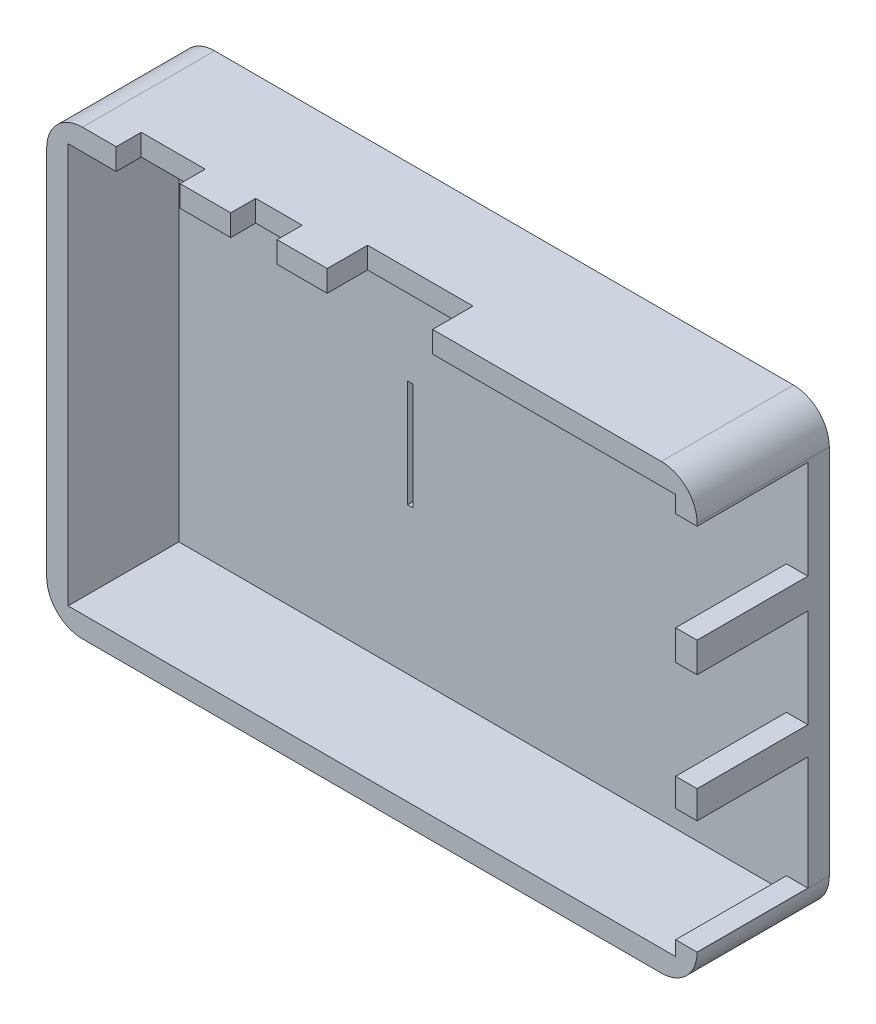
SolidWorks part; units mm, degrees
ref_plane "Front Plane" through (0, 0, 0) normal (0, 0, 1) x (1, 0, 0)
ref_plane "Top Plane" through (0, 0, 0) normal (0, 1, 0) x (1, 0, 0)
ref_plane "Right Plane" through (0, 0, 0) normal (1, 0, 0) x (0, 0, -1)
sketch "Sketch1" plane through (0, 0, 0) normal (0, 0, 1) x (1, 0, 0)
  line L1 (-45.5, -31) -> (45.5, -31)
  line L2 (-45.5, -31) -> (-45.5, 31)
  line L3 (-45.5, 31) -> (45.5, 31)
  line L4 (45.5, -31) -> (45.5, 31)
  line L5 (-45.5, -31) -> (45.5, 31) construction
  line L6 (-45.5, 31) -> (45.5, -31) construction
  point P0 (0, 0)
  dimension "D1" = 62
  dimension "D2" = 91
extrude "Boss-Extrude1" add sketch "Sketch1" along normal blind 3
sketch "Sketch2" plane through (0, 0, 3) normal (0, 0, 1) x (1, 0, 0)
  line L1 (-42.5, -28) -> (42.5, -28)
  line L2 (-42.5, -28) -> (-42.5, 28)
  line L3 (-42.5, 28) -> (42.5, 28)
  line L4 (42.5, -28) -> (42.5, 28)
  line L5 (-42.5, -28) -> (42.5, 28) construction
  line L6 (-42.5, 28) -> (42.5, -28) construction
  line L7 (-45.5, -31) -> (45.5, -31)
  line L8 (-45.5, -31) -> (-45.5, 31)
  line L9 (-45.5, 31) -> (45.5, 31)
  line L10 (45.5, -31) -> (45.5, 31)
  line L11 (-45.5, -31) -> (45.5, 31) construction
  line L12 (-45.5, 31) -> (45.5, -31) construction
  point P0 (0, 0)
  point P5 (0, 0)
  dimension "D1" = 56
  dimension "D2" = 85
extrude "Boss-Extrude2" add sketch "Sketch2" along normal blind 15.5
fillet "Fillet1" radius 5 4 edges at (45.5, -31, 9.25) (-45.5, -31, 9.25) (-45.5, 31, 9.25) (45.5, 31, 9.25)
sketch "Sketch3" plane through (0, 0, 18.5) normal (0, 0, 1) x (1, 0, 0)
  line L0 (45.5, -26) -> (45.5, 26) construction
  line L1 (45.5, -25.95) -> (42.5, -25.95)
  line L2 (45.5, -25.95) -> (45.5, -10.05)
  line L3 (45.5, -10.05) -> (42.5, -10.05)
  line L4 (42.5, -25.95) -> (42.5, -10.05)
  line L5 (42.5, -28) -> (42.5, 28) construction
  line L7 (45.5, -6.15) -> (42.5, -6.15)
  line L8 (45.5, -6.15) -> (45.5, 7.65)
  line L9 (45.5, 7.65) -> (42.5, 7.65)
  line L10 (42.5, -6.15) -> (42.5, 7.65)
  line L11 (45.5, 11.85) -> (42.5, 11.85)
  line L12 (45.5, 11.85) -> (45.5, 25.65)
  line L13 (45.5, 25.65) -> (42.5, 25.65)
  line L14 (42.5, 11.85) -> (42.5, 25.65)
  line L17 (42.5, 28) -> (-42.5, 28) construction
  dimension "D1" = 13.8
  dimension "D2" = 13.8
  dimension "D3" = 3.9
  dimension "D4" = 2.35
  dimension "D5" = 15.9
  dimension "D6" = 4.2
extrude "Cut-Extrude2" cut sketch "Sketch3" against normal blind 15.5
sketch "Sketch4" plane through (0, 0, 18.5) normal (0, 0, 1) x (1, 0, 0)
  line L6 (-42.5, 28) -> (-42.5, -28) construction
  line L15 (40.5, 31) -> (-40.5, 31) construction
  line L16 (-35.77, 31) -> (-26.83, 31)
  line L17 (-35.77, 31) -> (-35.77, 28)
  line L18 (-35.77, 28) -> (-26.83, 28)
  line L19 (-26.83, 31) -> (-26.83, 28)
  line L20 (42.5, 28) -> (-42.5, 28) construction
  line L22 (-19.75, 31) -> (-13.25, 31)
  line L23 (-19.75, 31) -> (-19.75, 28)
  line L24 (-19.75, 28) -> (-13.25, 28)
  line L25 (-13.25, 31) -> (-13.25, 28)
  line L26 (-6.25, 31) -> (0.25, 31)
  line L27 (-6.25, 31) -> (-6.25, 28)
  line L28 (-6.25, 28) -> (0.25, 28)
  line L29 (0.25, 31) -> (0.25, 28)
  dimension "D7" = 6.73
  dimension "D8" = 8.94
  dimension "D9" = 7.08
  dimension "D10" = 6.5
  dimension "D11" = 6.5
  dimension "D12" = 7
extrude "Cut-Extrude3" cut sketch "Sketch4" against normal blind 3.5
sketch "Sketch5" plane through (0, 0, 18.5) normal (0, 0, 1) x (1, 0, 0)
  line L5 (42.5, 28) -> (0.25, 28) construction
  line L6 (-6.25, 31) -> (8.5, 31)
  line L7 (-6.25, 31) -> (-6.25, 28)
  line L8 (-6.25, 28) -> (8.5, 28)
  line L9 (8.5, 31) -> (8.5, 28)
  dimension "D2" = 14.75
extrude "Cut-Extrude4" cut sketch "Sketch5" against normal blind 5.65
sketch "Sketch6" plane through (0, 0, 0) normal (0, 0, -1) x (-1, 0, 0)
  line L0 (-71.8015, 0) -> (81.5926, 0) construction
  line L1 (9.75, 7.5) -> (10.5, 7.5)
  line L2 (9.75, 7.5) -> (9.75, -7.5)
  line L3 (9.75, -7.5) -> (10.5, -7.5)
  line L4 (10.5, 7.5) -> (10.5, -7.5)
  line L5 (45.5, 26) -> (45.5, -26) construction
  point P7 (10.5, 0)
  dimension "D1" = 0.75
  dimension "D2" = 15
  dimension "D3" = 35
extrude "Cut-Extrude5" cut sketch "Sketch6" along direction (0, 0, -1) on the side against the normal up to surface (3 mm away)
